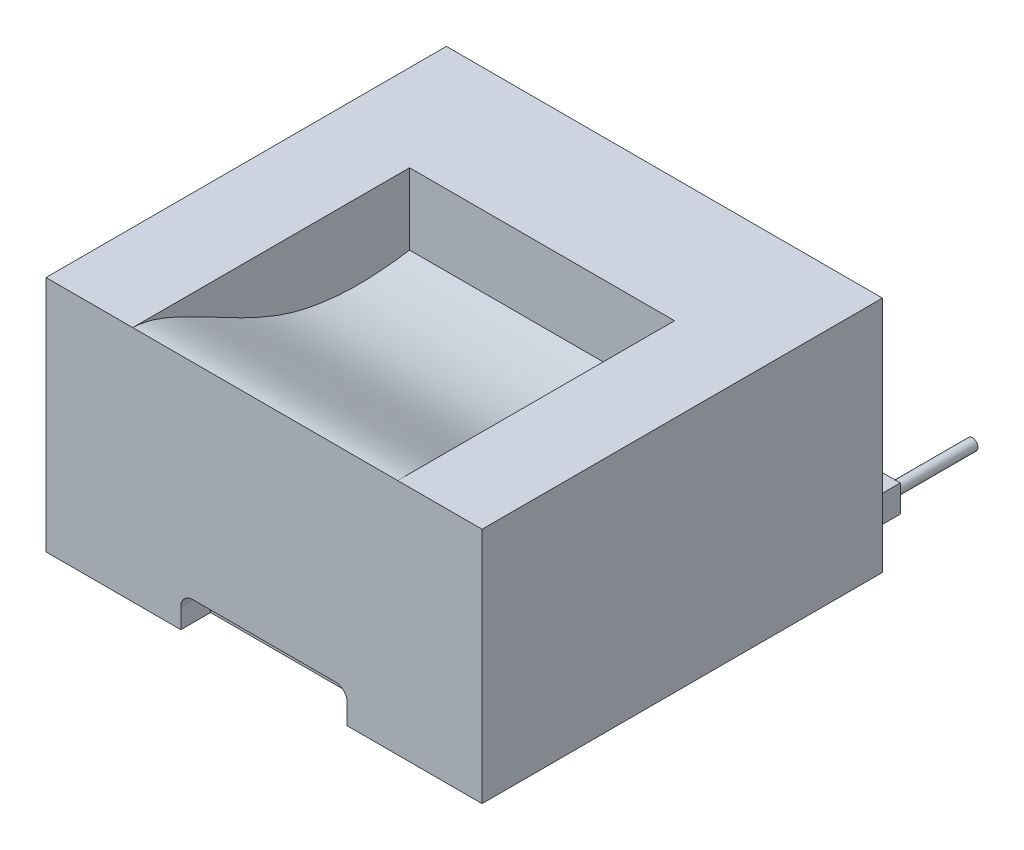
SolidWorks part; units mm, degrees
ref_plane "Front" through (0, 0, 0) normal (0, 0, 1) x (1, 0, 0)
ref_plane "Top" through (0, 0, 0) normal (0, 1, 0) x (1, 0, 0)
ref_plane "Right" through (0, 0, 0) normal (1, 0, 0) x (0, 0, -1)
sketch "Эскиз1" plane through (0, 0, 0) normal (0, 1, 0) x (1, 0, 0)
  line L1 (-199.7542, 47.1052) -> (167.2458, 47.1052)
  line L2 (-199.7542, 47.1052) -> (-199.7542, -289.8948)
  line L3 (-199.7542, -289.8948) -> (167.2458, -289.8948)
  line L4 (167.2458, 47.1052) -> (167.2458, -289.8948)
  dimension "D1" = 367
  dimension "D2" = 337
extrude "Бобышка-Вытянуть1" add sketch "Эскиз1" along normal blind 200
sketch "Эскиз2" plane through (0, 0, -47.1052) normal (0, 0, -1) x (-1, 0, 0)
  line L0 (-167.2458, 0) -> (199.7542, 0) construction
  line L1 (-106.2458, 0) -> (138.7542, 0)
  line L2 (-106.2458, 0) -> (-106.2458, 47)
  line L3 (-106.2458, 47) -> (138.7542, 47)
  line L4 (138.7542, 0) -> (138.7542, 47)
  line L5 (16.2542, 200) -> (16.2542, 0) construction
  line L6 (-167.2458, 200) -> (199.7542, 200) construction
  point P10 (16.2542, 0)
  dimension "D1" = 245
  dimension "D2" = 47
extrude "Бобышка-Вытянуть2" add sketch "Эскиз2" along normal blind 47
sketch "Эскиз3" plane through (0, 0, -47.1052) normal (0, 0, -1) x (-1, 0, 0)
  line L0 (-167.2458, 200) -> (-167.2458, 0) construction
  line L1 (-147.2458, 37.7594) -> (-128.7418, 37.7594)
  line L2 (-147.2458, 37.7594) -> (-147.2458, 15)
  line L3 (-147.2458, 15) -> (-128.7418, 15)
  line L4 (-128.7418, 37.7594) -> (-128.7418, 15)
  line L5 (-167.2458, 0) -> (-106.2458, 0) construction
  dimension "D1" = 20
  dimension "D2" = 15
extrude "Бобышка-Вытянуть3" add sketch "Эскиз3" along normal blind 35
sketch "Эскиз4" plane through (0, 0, -82.1052) normal (0, 0, -1) x (-1, 0, 0)
  line L0 (-147.2458, 37.7594) -> (-128.7418, 15) construction
  circle A0 centre (-137.9938, 26.3797) radius 4.6891
extrude "Бобышка-Вытянуть4" add sketch "Эскиз4" along normal blind 70
sketch "Эскиз5" plane through (0, 0, 289.8948) normal (0, 0, 1) x (1, 0, 0)
  line L0 (-199.7542, 0) -> (167.2458, 0) construction
  line L1 (-86.2542, 0) -> (53.7458, 0)
  line L2 (-86.2542, 0) -> (-86.2542, 17)
  line L3 (-76.2542, 27) -> (43.7458, 27)
  line L4 (53.7458, 0) -> (53.7458, 17)
  line L5 (-16.2542, 200) -> (-16.2542, 0) construction
  line L6 (-199.7542, 200) -> (167.2458, 200) construction
  arc A0 (43.7458, 27) -> (53.7458, 17) centre (43.7458, 17) cw
  arc A1 (-86.2542, 17) -> (-76.2542, 27) centre (-76.2542, 17) cw
  point P10 (-16.2542, 0)
  point P13 (53.7458, 27)
  point P16 (-86.2542, 27)
  dimension "D3" = 10
  dimension "D1" = 140
  dimension "D2" = 27
extrude "Вырез-Вытянуть1" cut sketch "Эскиз5" against normal blind 25
ref_plane "Плоскость1" through (96.2458, 0, 0) normal (1, 0, 0) x (0, 0, -1)
sketch "Эскиз6" plane through (96.2458, 0, 0) normal (1, 0, 0) x (0, 0, -1)
  line L0 (-289.8948, 200) -> (-56.8948, 200)
  line L1 (-289.8948, 200) -> (47.1052, 200) construction
  line L2 (-56.8948, 200) -> (-56.8948, 140)
  spline S0 degree 3 poles (-289.8948, 200) (-255.9059, 199.4831) (-195.6757, 150.5427) (-111.6301, 134.6802) (-84.5905, 135.8864) (-56.8948, 140) knots 0 0 0 0 0.585079 0.685079 1 1 1 1
  dimension "D1" = 233
  dimension "D2" = 60
extrude "Вырез-Вытянуть2" cut sketch "Эскиз6" against normal blind 223
sketch3d "Трехмерный эскиз1"
  line L0 (-16.2542, 200, -47.1052) -> (-16.2542, 200, 336.615) construction
  line L1 (167.2458, 200, -47.1052) -> (-199.7542, 200, -47.1052) construction
  line L6 (-199.7542, 200, 121.3948) -> (167.2458, 200, 121.3948) construction
  line L7 (-199.7542, 200, -47.1052) -> (-199.7542, 200, 289.8948) construction
  line L8 (167.2458, 200, 289.8948) -> (167.2458, 200, -47.1052) construction
  point P4 (0, 0, 0)
  point P7 (167.2458, 200, 121.3948)
  point P10 (0, 0, 0)
  point P11 (0, 0, 0)
  point P15 (-16.2542, 200, 121.3948)
ref_plane "Плоскость2" through (-16.2542, 0, 0) normal (1, 0, 0) x (0, 0, 1)
